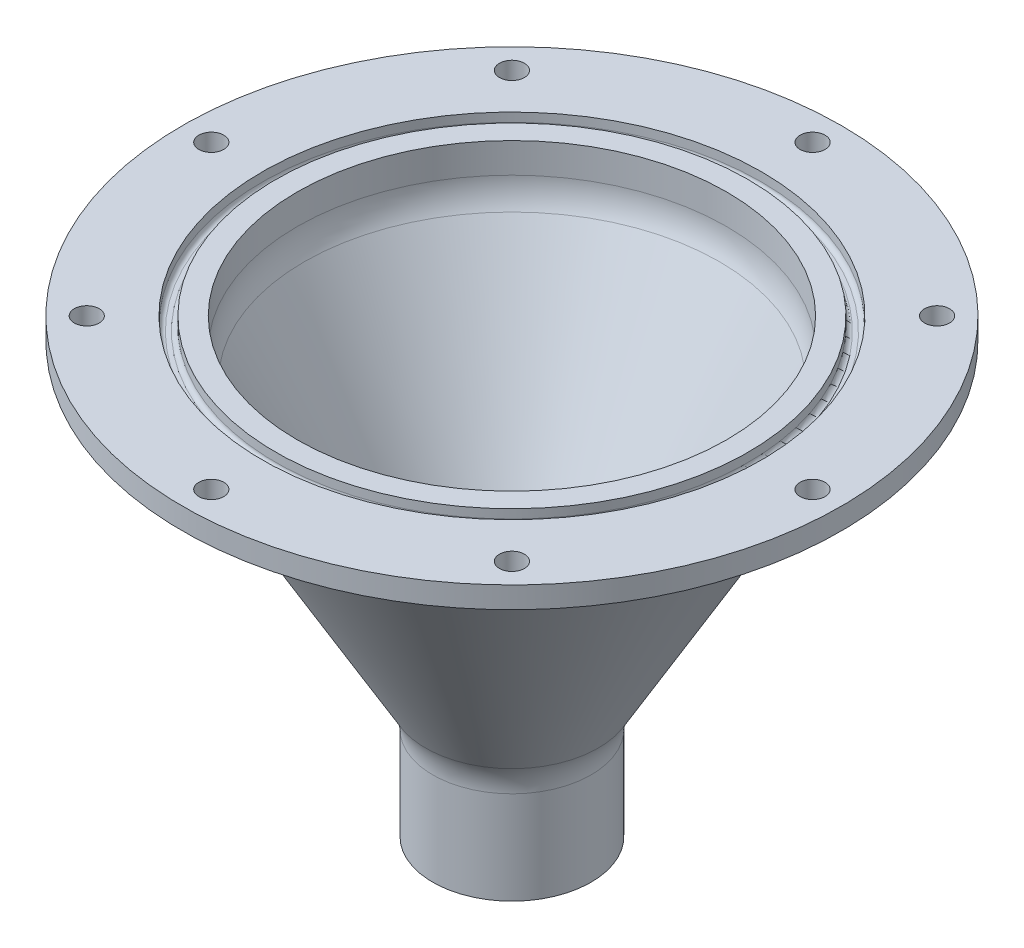
SolidWorks part; units mm, degrees
ref_plane "Front Plane" through (0, 0, 0) normal (0, 0, 1) x (1, 0, 0)
ref_plane "Top Plane" through (0, 0, 0) normal (0, 1, 0) x (1, 0, 0)
ref_plane "Right Plane" through (0, 0, 0) normal (1, 0, 0) x (0, 0, -1)
sketch "Sketch1" plane through (0, 0, 0) normal (0, 0, 1) x (1, 0, 0)
  line L0 (0, 0) -> (0, 76.2) construction
  line L1 (5.5562, 0) -> (5.5562, 12.0194)
  line L2 (6.407, 15.1944) -> (24.5493, 46.6177)
  line L3 (25.4, 53.34) -> (27.94, 53.34)
  line L4 (38.9833, 53.34) -> (38.9833, 50.8)
  line L5 (38.9833, 50.8) -> (33.1964, 50.8)
  line L6 (30.4468, 49.2125) -> (10.217, 14.1735)
  line L7 (9.3662, 10.9985) -> (9.3662, 0)
  line L8 (9.3662, 0) -> (5.5562, 0)
  line L9 (25.4, 49.7927) -> (25.4, 53.34)
  line L10 (27.94, 53.34) -> (27.94, 52.2923)
  line L11 (28.4798, 51.7525) -> (28.9877, 51.7525)
  line L12 (29.5275, 52.2923) -> (29.5275, 53.34)
  line L13 (29.5275, 53.34) -> (38.9833, 53.34)
  arc A0 (10.217, 14.1735) -> (9.3662, 10.9985) centre (15.7162, 10.9985) ccw
  arc A1 (33.1964, 50.8) -> (30.4468, 49.2125) centre (33.1964, 47.625) ccw
  arc A2 (24.5493, 46.6177) -> (25.4, 49.7927) centre (19.05, 49.7927) ccw
  arc A3 (5.5562, 12.0194) -> (6.407, 15.1944) centre (11.9062, 12.0194) cw
  arc A4 (28.9877, 51.7525) -> (29.5275, 52.2923) centre (28.9878, 52.2923) ccw
  arc A5 (27.94, 52.2923) -> (28.4798, 51.7525) centre (28.4798, 52.2923) ccw
  point P13 (9.3662, 12.7)
  point P16 (31.3633, 50.8)
  point P28 (29.5275, 51.7525)
  dimension "D10" = 6.35
  dimension "D12" = 6.35
  dimension "D13" = 3.175
  dimension "D17" = 0.5397
  dimension "D1" = 76.2
  dimension "D2" = 3.81
  dimension "D3" = 3.81
  dimension "D4" = 2.54
  dimension "D5" = 11.1125
  dimension "D6" = 30
  dimension "D7" = 7.62
  dimension "D8" = 12.7
  dimension "D9" = 38.1
  dimension "D11" = 25.4
  dimension "D14" = 1.5875
  dimension "D15" = 1.5875
  dimension "D16" = 27.94
revolve "Revolve1" add sketch "Sketch1" angle 360 about L0
hole_wizard "#4 Clearance Hole1" positions "Sketch3" profile "Sketch4" hole size "#4" standard "ANSI Inch"
sketch "Sketch3" plane through (0, 50.8, 0) normal (0, -1, 0) x (-1, 0, 0)
  circle A0 centre (0, 0) radius 35.56 construction
  point P0 (35.56, 0)
  point P3 (35.56, 0)
  point P17 (25.1447, -25.1447)
  point P18 (0, -35.56)
  point P19 (-25.1447, -25.1447)
  point P20 (-35.56, 0)
  point P21 (-25.1447, 25.1447)
  point P22 (0, 35.56)
  point P23 (25.1447, 25.1447)
  point P24 (0, 0)
  dimension "D1" = 71.12
  dimension "D2" = 8
sketch "Sketch4" plane through (-35.56, 50.8, 0) normal (1, 0, 0) x (0, 0, -1)
  line L0 (0, 0) -> (0, 39.2392)
  line L1 (0, 39.2392) -> (1.4732, 38.354)
  line L2 (1.4732, 38.354) -> (1.4732, 0)
  line L5 (1.4732, 0) -> (0, 0)
  line L10 (0, 39.2392) -> (-1.4732, 38.354) construction
  line L11 (0, -6.35) -> (0, 107.95) construction
  dimension "Hole Dia." = 2.9464
  dimension "Hole Depth" = 38.354
  dimension "Drill Angle" = 118
